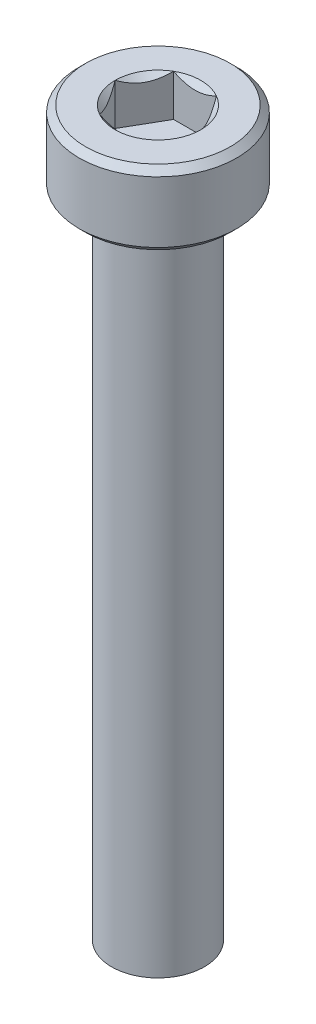
SolidWorks part; units mm, degrees
ref_plane "Front" through (0, 0, 0) normal (0, 0, 1) x (1, 0, 0)
ref_plane "Top" through (0, 0, 0) normal (0, 1, 0) x (1, 0, 0)
ref_plane "Right" through (0, 0, 0) normal (1, 0, 0) x (0, 0, -1)
sketch "Sketch1" plane through (0, 0, 0) normal (0, 1, 0) x (1, 0, 0)
  circle A0 centre (0, 0) radius 4.25
  dimension "D1" = 8.5
extrude "Boss-Extrude1" add sketch "Sketch1" along normal blind 4
sketch "Sketch2" plane through (0, 4, 0) normal (0, 1, 0) x (1, 0, 0)
  line L1 (1.1547, 2) -> (-1.1547, 2)
  line L2 (-1.1547, 2) -> (-2.3094, 0)
  line L3 (-2.3094, 0) -> (-1.1547, -2)
  line L4 (-1.1547, -2) -> (1.1547, -2)
  line L5 (1.1547, -2) -> (2.3094, 0)
  line L6 (2.3094, 0) -> (1.1547, 2)
  circle A0 centre (0, 0) radius 2 construction
  point P10 (0, 2)
  dimension "D1" = 4
extrude "Cut-Extrude1" cut sketch "Sketch2" against normal blind 2.25
sketch "Sketch3" plane through (0, 4, 0) normal (0, 1, 0) x (1, 0, 0)
  circle A0 centre (0, 0) radius 2.3094
extrude "Cut-Extrude2" cut sketch "Sketch3" against normal through all draft 45
chamfer "Chamfer1" distance 0.35 angle 45 2 edges at (0, 0, 4.25) (0, 4, 4.25)
sketch "草图1" plane through (0, 0, 0) normal (0, -1, 0) x (-1, 0, 0)
  circle A0 centre (0, 0) radius 2.5
  dimension "D1" = 5
extrude "凸台-拉伸1" add sketch "草图1" along normal blind 35
